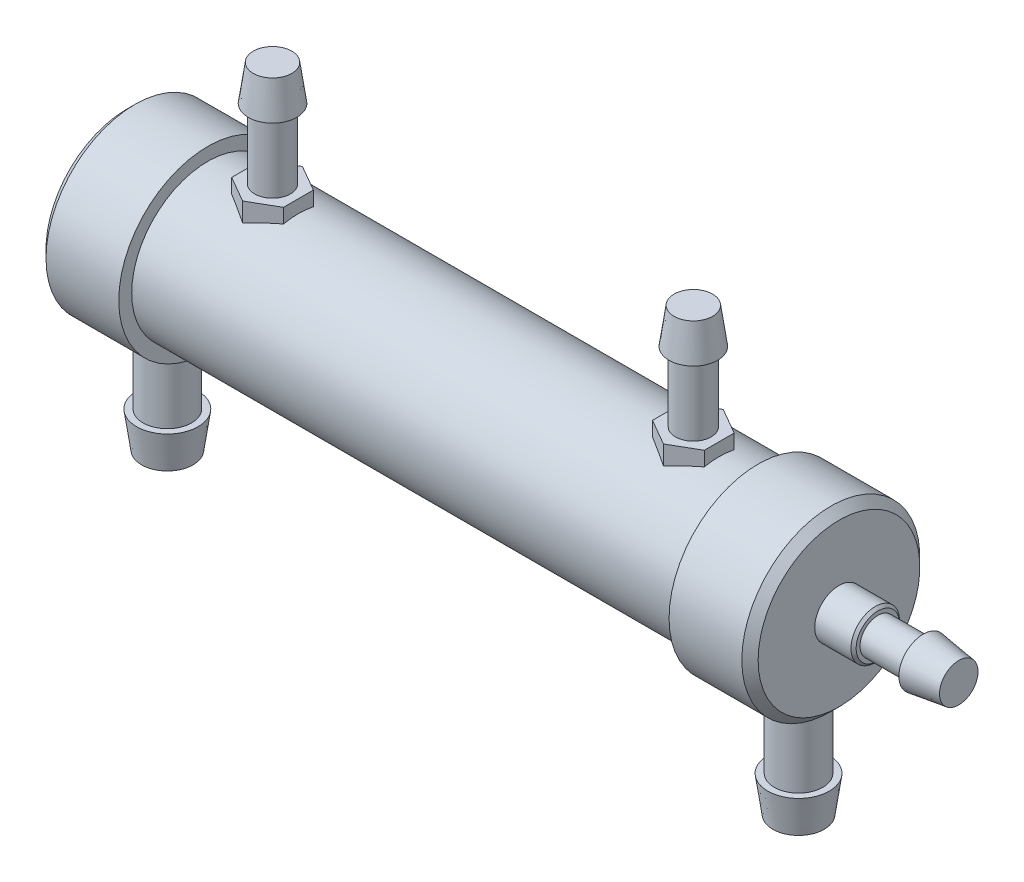
SolidWorks part; units mm, degrees
ref_plane "Front Plane" through (0, 0, 0) normal (0, 0, 1) x (1, 0, 0)
ref_plane "Top Plane" through (0, 0, 0) normal (0, 1, 0) x (1, 0, 0)
ref_plane "Right Plane" through (0, 0, 0) normal (1, 0, 0) x (0, 0, -1)
sketch "Sketch1" plane through (0, 0, 0) normal (0, 0, 1) x (1, 0, 0)
  line L0 (0, 0) -> (44839.0615, 0) construction
  line L1 (0, 0) -> (0, 17.4625)
  line L2 (0, 17.4625) -> (15.875, 17.4625)
  line L3 (15.875, 17.4625) -> (15.875, 14.9225)
  line L4 (15.875, 14.9225) -> (123.825, 14.9225)
  line L5 (123.825, 14.9225) -> (123.825, 17.4625)
  line L6 (123.825, 17.4625) -> (139.7, 17.4625)
  line L7 (139.7, 17.4625) -> (139.7, 4.7625)
  line L8 (163.195, 0) -> (0, 0)
  line L9 (139.7, 4.7625) -> (147.32, 4.7625)
  line L10 (147.32, 4.7625) -> (147.32, 3.4925)
  line L11 (147.32, 3.4925) -> (156.21, 3.4925)
  line L12 (156.21, 3.4925) -> (156.21, 4.7625)
  line L13 (156.21, 4.7625) -> (163.195, 3.7808)
  line L14 (163.195, 3.7808) -> (163.195, 0)
  dimension "D1" = 34.925
  dimension "D2" = 2.54
  dimension "D3" = 139.7
  dimension "D4" = 15.875
  dimension "D5" = 163.195
  dimension "D6" = 9.525
  dimension "D7" = 8.89
  dimension "D8" = 7.62
  dimension "D9" = 1.27
  dimension "D10" = 8
revolve "Revolve1" add sketch "Sketch1" angle 360 about L0
sketch "Sketch2" plane through (0, 0, 0) normal (0, 0, 1) x (1, 0, 0)
  line L0 (7.9375, -0.2613) -> (7.9375, -50000.2613) construction
  line L1 (0, 17.4625) -> (0, -17.4625) construction
  line L2 (12.7, -17.4625) -> (12.7, -31.115)
  line L3 (0, -17.4625) -> (15.875, -17.4625) construction
  line L4 (12.7, -31.115) -> (13.97, -31.115)
  line L5 (13.97, -31.115) -> (12.9883, -38.1)
  line L6 (12.9883, -38.1) -> (7.9375, -38.1)
  line L7 (7.9375, -38.1) -> (7.9375, -17.4625)
  line L8 (7.9375, -17.4625) -> (12.7, -17.4625)
  dimension "D1" = 7.9375
  dimension "D2" = 38.1
  dimension "D3" = 6.985
  dimension "D4" = 98
  dimension "D5" = 1.27
  dimension "D6" = 9.525
revolve "Revolve2" add sketch "Sketch2" angle 360 about L0
sketch "Sketch3" plane through (0, 0, 0) normal (0, 0, 1) x (1, 0, 0)
  line L0 (28.575, -0.8252) -> (28.575, 49999.1748) construction
  line L1 (25.0825, 14.9225) -> (25.0825, 31.115)
  line L2 (123.825, 14.9225) -> (15.875, 14.9225) construction
  line L3 (25.0825, 31.115) -> (23.8125, 31.115)
  line L4 (23.8125, 31.115) -> (24.7942, 38.1)
  line L5 (24.7942, 38.1) -> (28.575, 38.1)
  line L6 (28.575, 38.1) -> (28.575, 14.9225)
  line L7 (28.575, 14.9225) -> (25.0825, 14.9225)
  dimension "D1" = 28.575
  dimension "D2" = 9.525
  dimension "D3" = 8
  dimension "D4" = 6.985
  dimension "D5" = 1.27
  dimension "D6" = 38.1
revolve "Revolve3" add sketch "Sketch3" angle 360 about L0
ref_plane "Plane1" through (69.85, 0, 0) normal (-1, 0, 0) x (0, 0, 1)
mirror "Mirror4" about plane through (69.85, 0, 0) normal (-1, 0, 0) of bodies 102 103
sketch "Sketch4" plane through (0, 0, 0) normal (0, 1, 0) x (1, 0, 0)
  line L1 (33.655, -2.9329) -> (33.655, 2.9329)
  line L2 (33.655, 2.9329) -> (28.575, 5.8659)
  line L3 (28.575, 5.8659) -> (23.495, 2.9329)
  line L4 (23.495, 2.9329) -> (23.495, -2.9329)
  line L5 (23.495, -2.9329) -> (28.575, -5.8659)
  line L6 (28.575, -5.8659) -> (33.655, -2.9329)
  line L7 (111.125, -5.8659) -> (116.205, -2.9329)
  line L8 (116.205, -2.9329) -> (116.205, 2.9329)
  line L9 (116.205, 2.9329) -> (111.125, 5.8659)
  line L10 (111.125, 5.8659) -> (106.045, 2.9329)
  line L11 (106.045, 2.9329) -> (106.045, -2.9329)
  line L12 (106.045, -2.9329) -> (111.125, -5.8659)
  circle A0 centre (28.575, 0) radius 5.08 construction
  circle A1 centre (111.125, 0) radius 5.08 construction
  dimension "D1" = 10.16
extrude "Boss-Extrude1" add sketch "Sketch4" along normal blind 17.4625
chamfer "Chamfer1" distance 1.6002 angle 45 2 edges at (139.7, 0, 17.4625) (0, 0, 17.4625)
chamfer "Chamfer2" distance 0.508 angle 45 1 edges at (147.32, 0, 4.7625)
